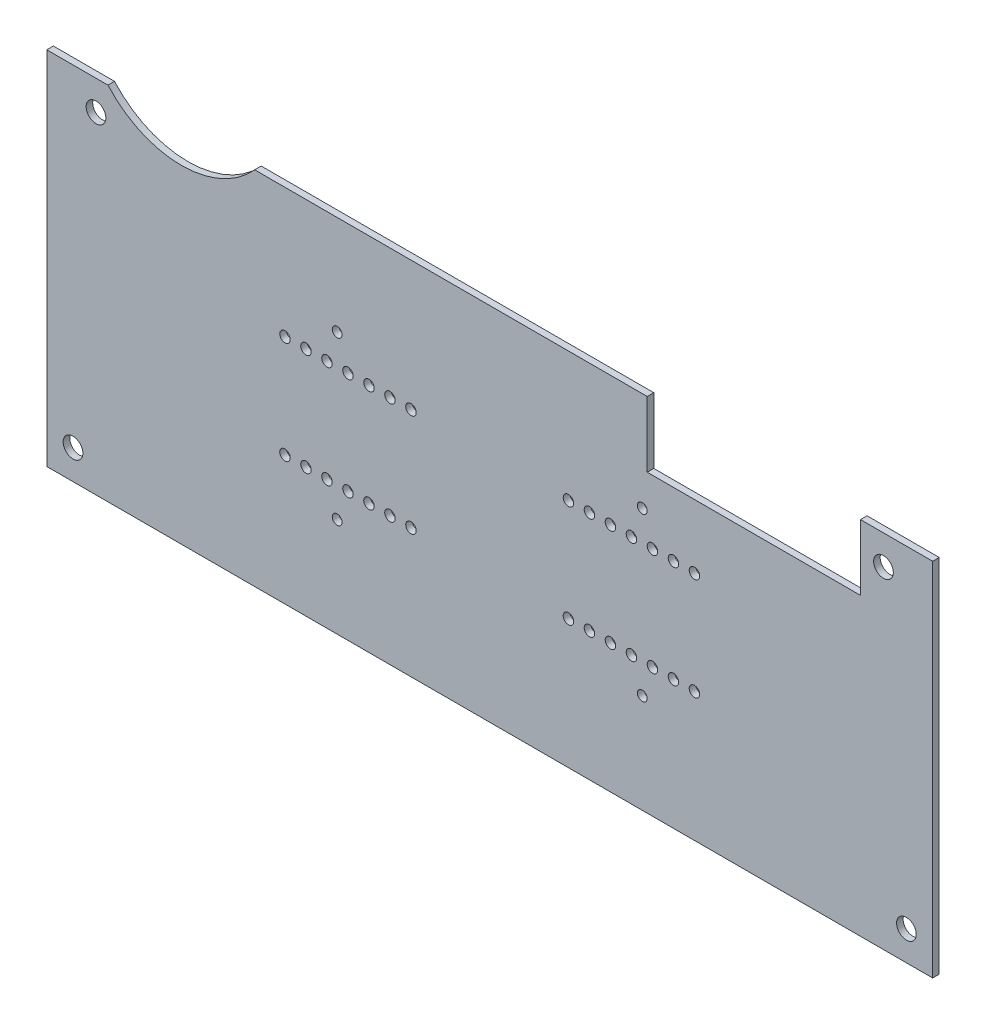
SolidWorks part; units mm, degrees
material "AISI 1020"
ref_plane "Front Plane" through (0, 0, 0) normal (0, 0, 1) x (1, 0, 0)
ref_plane "Top Plane" through (0, 0, 0) normal (0, 1, 0) x (1, 0, 0)
ref_plane "Right Plane" through (0, 0, 0) normal (1, 0, 0) x (0, 0, -1)
sketch "Sketch1" plane through (0, 0, 0) normal (0, 0, 1) x (1, 0, 0)
  line L1 (135, 55) -> (-135, 55)
  line L2 (135, 55) -> (135, -55)
  line L3 (135, -55) -> (-135, -55)
  line L4 (-135, 55) -> (-135, -55)
  line L5 (135, 55) -> (-135, -55) construction
  line L6 (135, -55) -> (-135, 55) construction
  point P0 (0, 0)
  dimension "D1" = 270
  dimension "D2" = 110
extrude "Boss-Extrude1" add sketch "Sketch1" along normal blind 2
sketch "Sketch5" plane through (0, 0, 2) normal (0, 0, 1) x (1, 0, 0)
  circle A4 centre (-46.5, 24.75) radius 1.5 construction
  circle A5 centre (46.5, 24.75) radius 1.5 construction
  circle A6 centre (46.5, -24.75) radius 1.5 construction
  circle A7 centre (-46.5, -24.75) radius 1.5 construction
  circle A8 centre (-46.5, 24.75) radius 1.5
  circle A9 centre (46.5, 24.75) radius 1.5
  circle A10 centre (46.5, -24.75) radius 1.5
  circle A11 centre (-46.5, -24.75) radius 1.5
extrude "Cut-Extrude3" cut sketch "Sketch5" against normal through all
sketch "Sketch6" plane through (0, 0, 2) normal (0, 0, 1) x (1, 0, 0)
  line L0 (0, 0) -> (0, -55) construction
  line L1 (-135, -55) -> (135, -55) construction
  circle A0 centre (-24, 15.5494) radius 1.6 construction
  circle A1 centre (-30.4, 15.5494) radius 1.6 construction
  circle A2 centre (-36.8, 15.5494) radius 1.6 construction
  circle A3 centre (-43.2, 15.5494) radius 1.6 construction
  circle A4 centre (-49.6, 15.5494) radius 1.6 construction
  circle A5 centre (-56, 15.5494) radius 1.6 construction
  circle A6 centre (-62.4, 15.5494) radius 1.6 construction
  circle A7 centre (-62.4, -15.6506) radius 1.6 construction
  circle A8 centre (-56, -15.6506) radius 1.6 construction
  circle A9 centre (-49.6, -15.6506) radius 1.6 construction
  circle A10 centre (-43.2, -15.6506) radius 1.6 construction
  circle A11 centre (-36.8, -15.6506) radius 1.6 construction
  circle A12 centre (-30.4, -15.6506) radius 1.6 construction
  circle A13 centre (-24, -15.6506) radius 1.6 construction
  circle A14 centre (-24, 15.5494) radius 1.6
  circle A15 centre (-30.4, 15.5494) radius 1.6
  circle A16 centre (-36.8, 15.5494) radius 1.6
  circle A17 centre (-43.2, 15.5494) radius 1.6
  circle A18 centre (-49.6, 15.5494) radius 1.6
  circle A19 centre (-56, 15.5494) radius 1.6
  circle A20 centre (-62.4, 15.5494) radius 1.6
  circle A21 centre (-62.4, -15.6506) radius 1.6
  circle A22 centre (-56, -15.6506) radius 1.6
  circle A23 centre (-49.6, -15.6506) radius 1.6
  circle A24 centre (-43.2, -15.6506) radius 1.6
  circle A25 centre (-36.8, -15.6506) radius 1.6
  circle A26 centre (-30.4, -15.6506) radius 1.6
  circle A27 centre (-24, -15.6506) radius 1.6
  circle A28 centre (24, -15.6506) radius 1.6
  circle A29 centre (30.4, -15.6506) radius 1.6
  circle A30 centre (36.8, -15.6506) radius 1.6
  circle A31 centre (43.2, -15.6506) radius 1.6
  circle A32 centre (49.6, -15.6506) radius 1.6
  circle A33 centre (56, -15.6506) radius 1.6
  circle A34 centre (62.4, -15.6506) radius 1.6
  circle A35 centre (62.4, 15.5494) radius 1.6
  circle A36 centre (56, 15.5494) radius 1.6
  circle A37 centre (49.6, 15.5494) radius 1.6
  circle A38 centre (43.2, 15.5494) radius 1.6
  circle A39 centre (36.8, 15.5494) radius 1.6
  circle A40 centre (30.4, 15.5494) radius 1.6
  circle A41 centre (24, 15.5494) radius 1.6
extrude "Cut-Extrude4" cut sketch "Sketch6" against normal through all
sketch "Sketch7" plane through (0, 0, 0) normal (0, 0, -1) x (-1, 0, 0)
  circle A0 centre (127, -46) radius 3 construction
  circle A1 centre (-120, 46) radius 3
  circle A2 centre (-120, 46) radius 3
  circle A3 centre (120, 46) radius 3 construction
  circle A4 centre (-127, -46) radius 3 construction
  circle A5 centre (127, -46) radius 3
  circle A6 centre (120, 46) radius 3
  circle A7 centre (-127, -46) radius 3
  dimension "D1" = 0
extrude "Cut-Extrude5" cut sketch "Sketch7" against normal blind 10
sketch "Sketch8" plane through (0, 0, 0) normal (0, 0, -1) x (-1, 0, 0)
  line L0 (135, 55) -> (135, -55) construction
  line L1 (-135, 55) -> (135, 55) construction
  line L2 (-135, -55) -> (-135, 55) construction
  line L3 (-48, 55) -> (-113, 55)
  line L4 (-48, 55) -> (-48, 35)
  line L5 (-48, 35) -> (-113, 35)
  line L6 (-113, 55) -> (-113, 35)
  circle A0 centre (94, 75) radius 30
  dimension "D1" = 60
  dimension "D2" = 41
  dimension "D3" = 20
  dimension "D4" = 65
  dimension "D5" = 22
  dimension "D6" = 20
extrude "Cut-Extrude6" cut sketch "Sketch8" against normal blind 10
